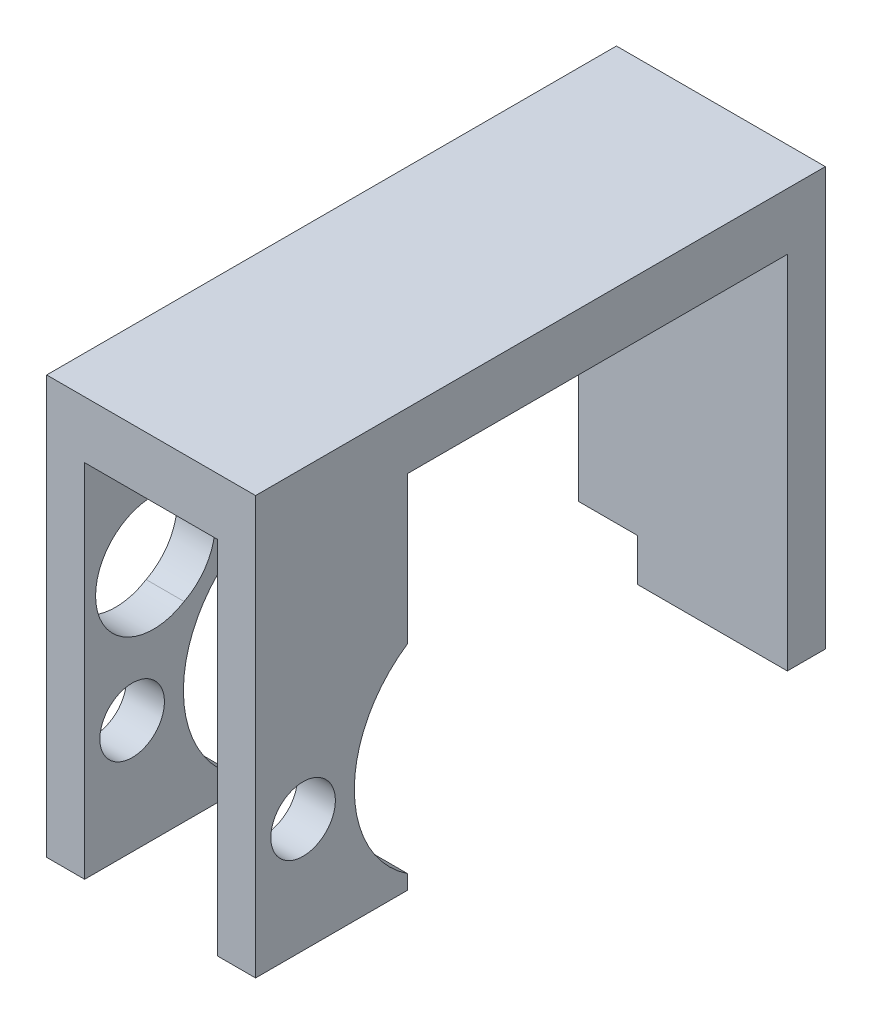
SolidWorks part; units mm, degrees
other "Preload Manual Lock Fork"
other "Preload Manual Lock Fork Left"
ref_plane "Front Plane" through (0, 0, 0) normal (0, 0, 1) x (1, 0, 0)
ref_plane "Top Plane" through (0, 0, 0) normal (0, 1, 0) x (1, 0, 0)
ref_plane "Right Plane" through (0, 0, 0) normal (1, 0, 0) x (0, 0, -1)
sketch3d "Rear lock ear sketch datum points"
  point P0 (-12, -45, -16)
  point P1 (-2, -45, -16)
  point P2 (-12, -35, -16)
ref_plane "Rear lock ear sketch plane" through (0, 0, -16) normal (0, 0, 1) x (1, 0, 0)
sketch "Rear lock ear sketch" plane through (0, 0, -16) normal (0, 0, 1) x (1, 0, 0)
  line L0 (-12, -45) -> (-10, -45)
  line L1 (-10, -45) -> (-10, -23)
  line L2 (-10, -23) -> (-12, -23)
  line L3 (-12, -23) -> (-12, -45)
extrude "Rear lock ear" add sketch "Rear lock ear sketch" along normal blind 8 separate body
sketch3d "Lock fork web sketch datum points"
  point P0 (-12, -45, -38)
  point P1 (-2, -45, -38)
  point P2 (-12, -35, -38)
ref_plane "Lock fork web sketch plane" through (0, 0, -38) normal (0, 0, 1) x (1, 0, 0)
sketch "Lock fork web sketch" plane through (0, 0, -38) normal (0, 0, 1) x (1, 0, 0)
  line L0 (-12, -45) -> (-1, -45)
  line L1 (-1, -45) -> (-1, -42)
  line L2 (-1, -42) -> (-12, -42)
  line L3 (-12, -42) -> (-12, -45)
extrude "Lock fork web" add sketch "Lock fork web sketch" along normal blind 30
sketch3d "Front lock ear sketch datum points"
  point P0 (-3, -45, -16)
  point P1 (7, -45, -16)
  point P2 (-3, -35, -16)
ref_plane "Front lock ear sketch plane" through (0, 0, -16) normal (0, 0, 1) x (1, 0, 0)
sketch "Front lock ear sketch" plane through (0, 0, -16) normal (0, 0, 1) x (1, 0, 0)
  line L0 (-3, -45) -> (-1, -45)
  line L1 (-1, -45) -> (-1, -23)
  line L2 (-1, -23) -> (-3, -23)
  line L3 (-3, -23) -> (-3, -45)
extrude "Front lock ear" add sketch "Front lock ear sketch" along normal blind 8
sketch3d "Fork mounting foot sketch datum points"
  point P0 (-12, -45, -38)
  point P1 (-2, -45, -38)
  point P2 (-12, -35, -38)
ref_plane "Fork mounting foot sketch plane" through (0, 0, -38) normal (0, 0, 1) x (1, 0, 0)
sketch "Fork mounting foot sketch" plane through (0, 0, -38) normal (0, 0, 1) x (1, 0, 0)
  line L0 (-12, -45) -> (-1, -45)
  line L1 (-1, -45) -> (-1, -23)
  line L2 (-1, -23) -> (-12, -23)
  line L3 (-12, -23) -> (-12, -45)
extrude "Fork mounting foot" add sketch "Fork mounting foot sketch" along normal blind 2
sketch3d "Coupling barrel clearance sketch datum points"
  point P0 (-12.1, -29, -19.5)
  point P1 (-12.1, -19, -19.5)
  point P2 (-12.1, -29, -9.5)
ref_plane "Coupling barrel clearance sketch plane" through (-12.1, 0, 0) normal (1, 0, 0) x (0, 0, -1)
sketch "Coupling barrel clearance sketch" plane through (-12.1, 0, 0) normal (1, 0, 0) x (0, 0, -1)
  circle A0 centre (19.5, -29) radius 6.3
extrude "Coupling barrel clearance" cut sketch "Coupling barrel clearance sketch" along normal blind 11.3
sketch3d "Service pin clearance 1 sketch datum points"
  point P0 (-12.1, -29, -10.5)
  point P1 (-12.1, -19, -10.5)
  point P2 (-12.1, -29, -0.5)
ref_plane "Service pin clearance 1 sketch plane" through (-12.1, 0, 0) normal (1, 0, 0) x (0, 0, -1)
sketch "Service pin clearance 1 sketch" plane through (-12.1, 0, 0) normal (1, 0, 0) x (0, 0, -1)
  circle A0 centre (10.5, -29) radius 1.7
extrude "Service pin clearance 1" cut sketch "Service pin clearance 1 sketch" along normal blind 2.3
sketch3d "Service pin clearance 2 sketch datum points"
  point P0 (-3.1, -29, -10.5)
  point P1 (-3.1, -19, -10.5)
  point P2 (-3.1, -29, -0.5)
ref_plane "Service pin clearance 2 sketch plane" through (-3.1, 0, 0) normal (1, 0, 0) x (0, 0, -1)
sketch "Service pin clearance 2 sketch" plane through (-3.1, 0, 0) normal (1, 0, 0) x (0, 0, -1)
  circle A0 centre (10.5, -29) radius 1.7
extrude "Service pin clearance 2" cut sketch "Service pin clearance 2 sketch" along normal blind 2.3
sketch3d "Motor head access 1-1 sketch datum points"
  point P0 (-12.1, -22.5, -34.765)
  point P1 (-12.1, -12.5, -34.765)
  point P2 (-12.1, -22.5, -24.765)
ref_plane "Motor head access 1-1 sketch plane" through (-12.1, 0, 0) normal (1, 0, 0) x (0, 0, -1)
sketch "Motor head access 1-1 sketch" plane through (-12.1, 0, 0) normal (1, 0, 0) x (0, 0, -1)
  circle A0 centre (34.765, -22.5) radius 3
extrude "Motor head access 1-1" cut sketch "Motor head access 1-1 sketch" along normal blind 3.2
sketch3d "Motor head access 1-5 sketch datum points"
  point P0 (-12.1, -35.7199, -11.8675)
  point P1 (-12.1, -25.7199, -11.8675)
  point P2 (-12.1, -35.7199, -1.8675)
ref_plane "Motor head access 1-5 sketch plane" through (-12.1, 0, 0) normal (1, 0, 0) x (0, 0, -1)
sketch "Motor head access 1-5 sketch" plane through (-12.1, 0, 0) normal (1, 0, 0) x (0, 0, -1)
  circle A0 centre (11.8675, -35.7199) radius 3
extrude "Motor head access 1-5" cut sketch "Motor head access 1-5 sketch" along normal blind 3.2
sketch3d "Motor head access 2-1 sketch datum points"
  point P0 (-12.1, -22, -35.25)
  point P1 (-12.1, -12, -35.25)
  point P2 (-12.1, -22, -25.25)
ref_plane "Motor head access 2-1 sketch plane" through (-12.1, 0, 0) normal (1, 0, 0) x (0, 0, -1)
sketch "Motor head access 2-1 sketch" plane through (-12.1, 0, 0) normal (1, 0, 0) x (0, 0, -1)
  circle A0 centre (35.25, -22) radius 3.05
extrude "Motor head access 2-1" cut sketch "Motor head access 2-1 sketch" along normal blind 3.2
sketch3d "Motor head access 2-5 sketch datum points"
  point P0 (-12.1, -35.6399, -11.625)
  point P1 (-12.1, -25.6399, -11.625)
  point P2 (-12.1, -35.6399, -1.625)
ref_plane "Motor head access 2-5 sketch plane" through (-12.1, 0, 0) normal (1, 0, 0) x (0, 0, -1)
sketch "Motor head access 2-5 sketch" plane through (-12.1, 0, 0) normal (1, 0, 0) x (0, 0, -1)
  circle A0 centre (11.625, -35.6399) radius 3.05
extrude "Motor head access 2-5" cut sketch "Motor head access 2-5 sketch" along normal blind 3.2
sketch3d "Mirror1 profile datum points"
  point P0 (0, 0, 0)
  point P1 (10, 0, 0)
  point P2 (0, 0, 10)
ref_plane "Mirror1 profile plane" through (0, 0, 0) normal (0, -1, 0) x (-1, 0, 0)
mirror "Mirror1" about plane through (0, 0, 0) normal (0, -1, 0) of bodies 111
delete or keep bodies "Remove1" type delete bodies bodies 111
